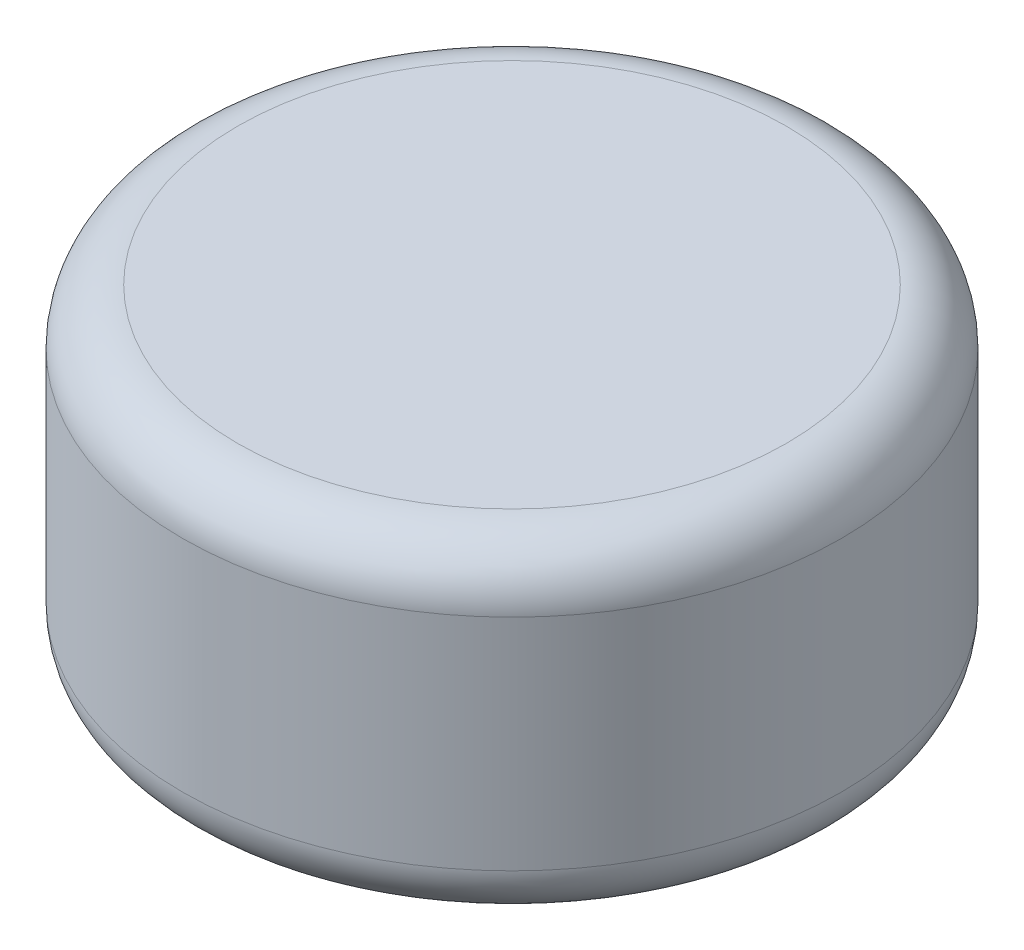
SolidWorks part; units mm, degrees
ref_plane "Front Plane" through (0, 0, 0) normal (0, 0, 1) x (1, 0, 0)
ref_plane "Top Plane" through (0, 0, 0) normal (0, 1, 0) x (1, 0, 0)
ref_plane "Right Plane" through (0, 0, 0) normal (1, 0, 0) x (0, 0, -1)
sketch "Sketch2" plane through (0, 0, 0) normal (0, 1, 0) x (1, 0, 0)
  circle A0 centre (0, 0) radius 3
  dimension "D1" = 6
extrude "Boss-Extrude1" add sketch "Sketch2" along normal blind 3
fillet "Fillet1" radius 0.5 1 edges at (0, 3, 3)
fillet "Fillet2" radius 0.5 1 edges at (0, 0, 3)
